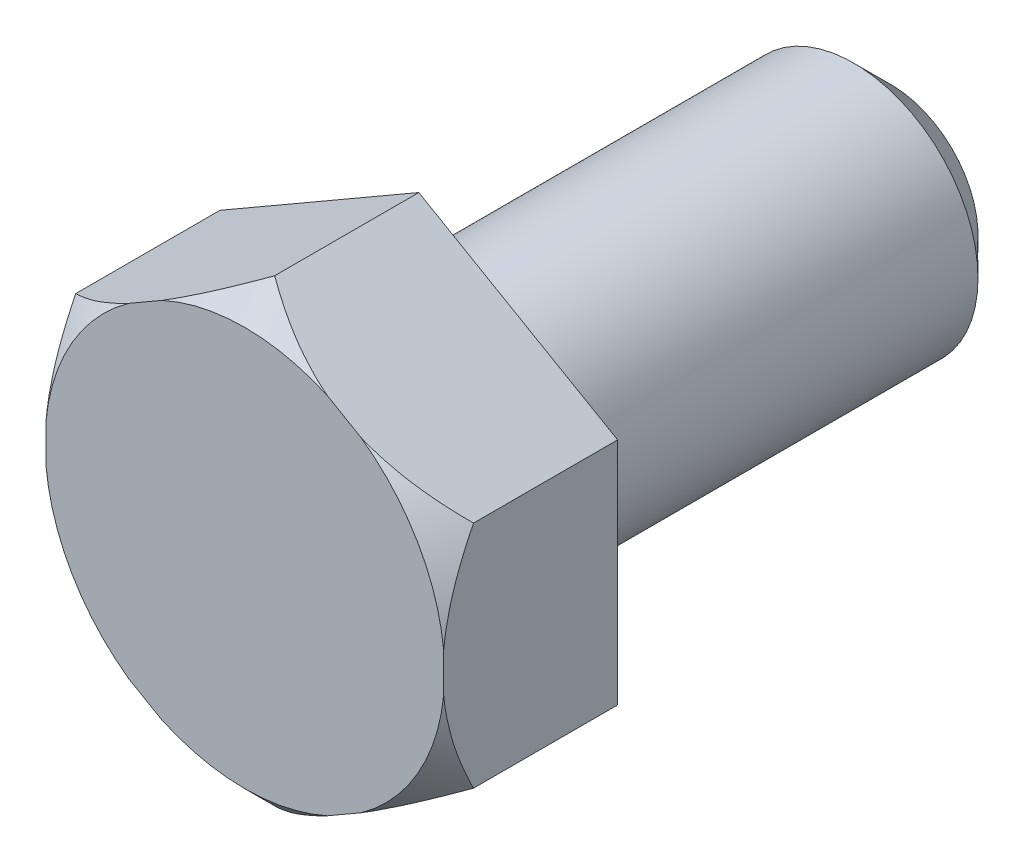
SolidWorks part; units mm, degrees
ref_plane "Спереди" through (0, 0, 0) normal (0, 0, 1) x (1, 0, 0)
ref_plane "Сверху" through (0, 0, 0) normal (0, 1, 0) x (1, 0, 0)
ref_plane "Справа" through (0, 0, 0) normal (1, 0, 0) x (0, 0, -1)
sketch "Эскиз1" plane through (0, 0, 0) normal (0, 0, 1) x (1, 0, 0)
  line L0 (0, 4.93) -> (0, -5.4719) construction
  line L1 (-5.0323, 0) -> (5.1026, 0) construction
  line L3 (0, 4.6188) -> (-4, 2.3094)
  line L4 (-4, 2.3094) -> (-4, -2.3094)
  line L5 (-4, -2.3094) -> (0, -4.6188)
  line L6 (0, -4.6188) -> (4, -2.3094)
  line L7 (4, -2.3094) -> (4, 2.3094)
  line L8 (4, 2.3094) -> (0, 4.6188)
  circle A0 centre (0, 0) radius 4 construction
extrude "Вытянуть1" add sketch "Эскиз1" along normal blind 3.5
sketch "Эскиз2" plane through (0, 0, 0) normal (0, 0, -1) x (-1, 0, 0)
  circle A0 centre (0, 0) radius 2.5
extrude "Вытянуть2" add sketch "Эскиз2" along normal blind 9.5
ref_axis "Ось4" through (0, 0, 2.9653) along (0, 0, -1)
sketch "Эскиз15" plane through (0, 0, 0) normal (1, 0, 0) x (0, 0, -1)
  line L0 (-3.5, 4.6188) -> (-3.5, 4.0188)
  line L1 (-3.5, 2.3094) -> (-3.5, 4.6188) construction
  line L2 (-3.5, 4.0188) -> (-2.9, 4.6188)
  line L3 (-3.5, 4.6188) -> (0, 4.6188) construction
  line L4 (-2.9, 4.6188) -> (-3.5, 4.6188)
revolve "Вырез-Повернуть1" cut sketch "Эскиз15" angle 360 about axis through (0, 0, 2.9653) along (0, 0, -1)
ref_plane "Плоскость1" through (4, 0.3883, 3.5) normal (-0.0966, 0.9953, 0) x (-0.9953, -0.0966, 0)
chamfer "Фаска1" distance 0.75 angle 45 1 edges at (-2.5, 0, -9.5)
